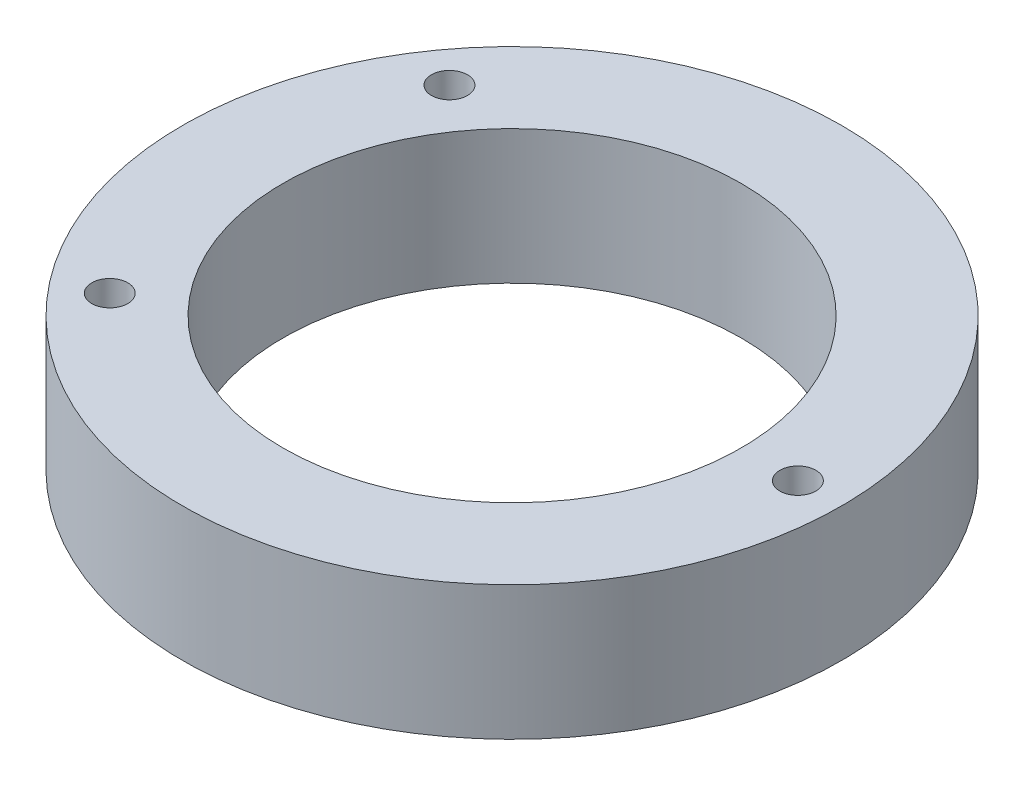
SolidWorks part; units mm, degrees
ref_plane "Front Plane" through (0, 0, 0) normal (0, 0, 1) x (1, 0, 0)
ref_plane "Top Plane" through (0, 0, 0) normal (0, 1, 0) x (1, 0, 0)
ref_plane "Right Plane" through (0, 0, 0) normal (1, 0, 0) x (0, 0, -1)
sketch "Sketch1" plane through (0, 0, 0) normal (0, 1, 0) x (1, 0, 0)
  line L0 (0, 0) -> (-50000, 0) construction
  line L1 (0, 0) -> (-22.4248, 16.3459) construction
  line L2 (0, 0) -> (-21.4215, -17.6403) construction
  circle A0 centre (0, 0) radius 32
  circle A1 centre (0, 0) radius 22.25
  circle A2 centre (27.75, 0) radius 1.75
  circle A3 centre (-22.4248, 16.3459) radius 1.75
  circle A4 centre (-21.4215, -17.6403) radius 1.75
  dimension "D1" = 64
  dimension "D2" = 44.5
  dimension "D4" = 3.5
  dimension "D3" = 27.75
  dimension "D5" = 75.56
  dimension "D6" = 27.75
  dimension "D7" = 27.75
extrude "Boss-Extrude1" add sketch "Sketch1" along normal blind 13
